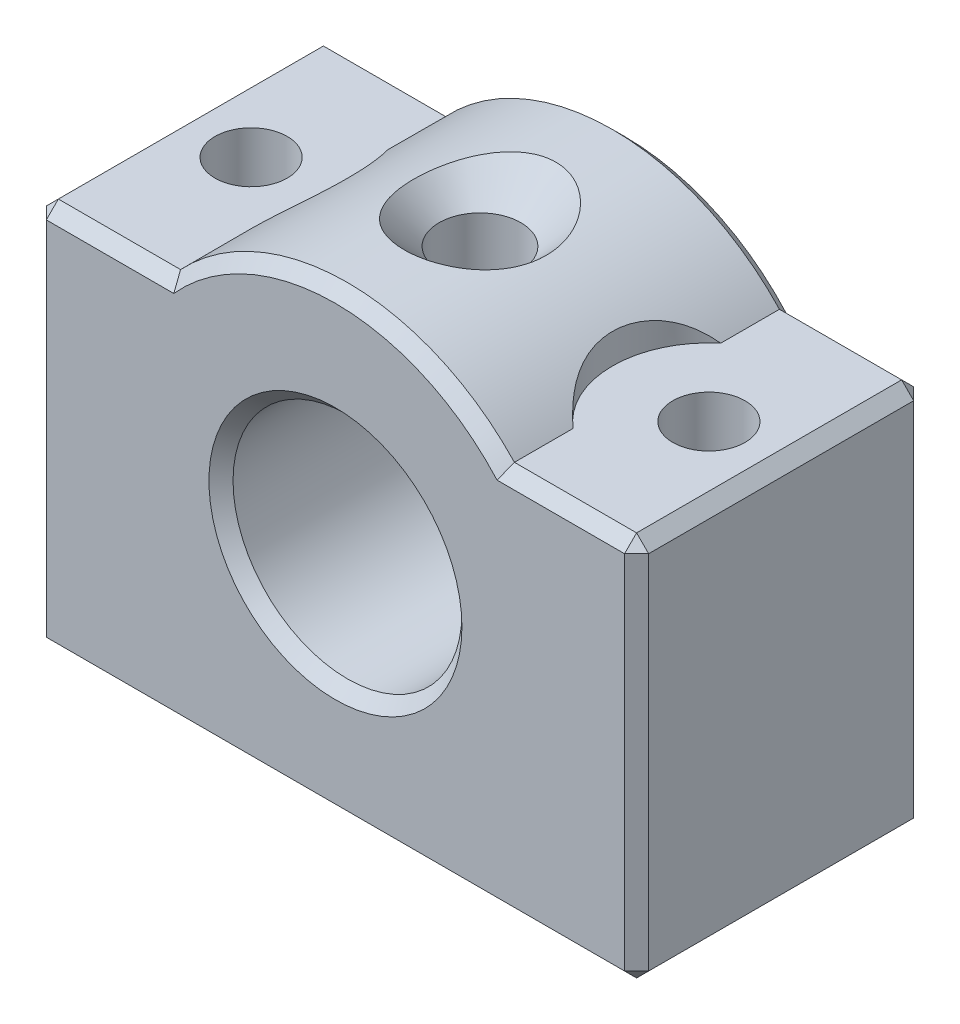
SolidWorks part; units mm, degrees
material "Commercial Bronze, UNS C22000 (90-10 Bronze)"
ref_plane "Front Plane" through (0, 0, 0) normal (0, 0, 1) x (1, 0, 0)
ref_plane "Top Plane" through (0, 0, 0) normal (0, 1, 0) x (1, 0, 0)
ref_plane "Right Plane" through (0, 0, 0) normal (1, 0, 0) x (0, 0, -1)
sketch "Sketch1" plane through (0, 0, 0) normal (0, 0, 1) x (1, 0, 0)
  line L0 (6.9282, 16) -> (12.5, 16)
  line L1 (-12.5, 16) -> (-6.9282, 16)
  line L2 (-12.5, 16) -> (-12.5, 0)
  line L3 (-12.5, 0) -> (12.5, 0)
  line L4 (12.5, 16) -> (12.5, 0)
  line L5 (-12.5, 16) -> (12.5, 0) construction
  line L6 (-12.5, 0) -> (12.5, 16) construction
  circle A0 centre (0, 9.5) radius 4.75
  arc A2 (6.9282, 16) -> (-6.9282, 16) centre (0, 9.5) ccw
  point P0 (0, 8)
  dimension "D3" = 9.5
  dimension "D5" = 9.5
  dimension "D1" = 16
  dimension "D2" = 12.5
  dimension "D4" = 9.5
extrude "Boss-Extrude1" add sketch "Sketch1" along normal mid plane 12
sketch "Sketch2" plane through (0, 16, 0) normal (0, 1, 0) x (1, 0, 0)
  line L0 (-6.9282, -6) -> (-12.5, -6) construction
  circle A0 centre (-9.5, 0) radius 1.5
  circle A1 centre (9.5, 0) radius 1.5
  dimension "D1" = 3
  dimension "D2" = 9.5
  dimension "D3" = 6
  dimension "D4" = 9.5
extrude "Cut-Extrude1" cut sketch "Sketch2" against normal up to next
sketch "Sketch3" plane through (0, 16, 0) normal (0, 1, 0) x (1, 0, 0)
  line L0 (6.9282, -6) -> (6.9282, 6) construction
  line L1 (-6.9282, -6) -> (-6.9282, 6) construction
  line L2 (6.9282, -3.0636) -> (6.9282, 3.0636)
  line L3 (-6.9282, -3.0636) -> (-6.9282, 3.0636)
  arc A0 (-6.9282, -3.0636) -> (-6.9282, 3.0636) centre (-9.5, 0) ccw
  arc A1 (6.9282, 3.0636) -> (6.9282, -3.0636) centre (9.5, 0) ccw
  dimension "D1" = 8
  dimension "D2" = 8
extrude "Cut-Extrude2" cut sketch "Sketch3" along normal blind 3
ref_plane "Plane1" through (0, 19, 0) normal (0, 1, 0) x (1, 0, 0)
sketch "Sketch7" plane through (0, 19, 0) normal (0, 1, 0) x (1, 0, 0)
  point P0 (0, 0)
hole_wizard "CSK for M3 Flat Head Machine Screw1" positions "Sketch7" profile "Sketch6" countersink size "M3" standard "ANSI Metric"
sketch "Sketch6" plane through (0, 19, 0) normal (1, 0, 0) x (0, 0, 1)
  line L0 (0, 0) -> (0, 10.0215)
  line L1 (0, 10.0215) -> (1.7, 9)
  line L2 (1.7, 9) -> (1.7, 1.45)
  line L3 (1.7, 1.45) -> (3.15, 0)
  line L5 (3.15, 0) -> (0, 0)
  line L6 (-1.7, 1.45) -> (-3.15, 0) construction
  line L10 (0, 10.0215) -> (-1.7, 9) construction
  line L11 (0, -6.35) -> (0, 107.95) construction
  dimension "Hole Dia." = 3.4
  dimension "Hole Depth" = 9
  dimension "Near C'Sink Dia." = 6.3
  dimension "Near C'Sink Angle" = 90
  dimension "Drill Angle" = 118
chamfer "Chamfer1" distance 0.5 angle 45 18 edges at (4.75, 9.5, -6) (4.75, 9.5, 6) (-12.5, 16, 0) (-12.5, 0, 0) (9.7141, 16, -6) (0, 19, -6) (-9.7141, 16, -6) (-12.5, 8, -6) (0, 0, -6) (12.5, 0, 0) (12.5, 8, -6) (12.5, 16, 0) (0, 0, 6) (-12.5, 8, 6) (-9.7141, 16, 6) (0, 19, 6) (9.7141, 16, 6) (12.5, 8, 6)
